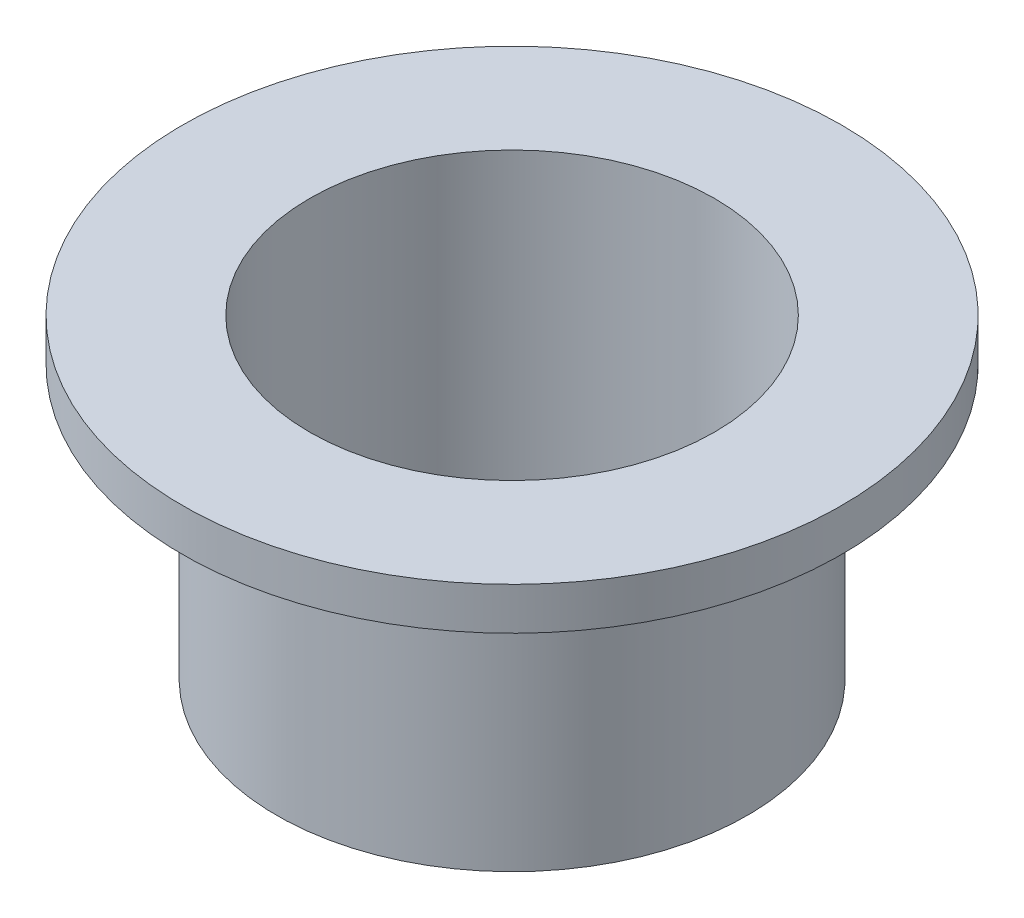
SolidWorks part; units mm, degrees
ref_plane "Front Plane" through (0, 0, 0) normal (1, 0, 0) x (0, 1, 0)
ref_plane "Top Plane" through (0, 0, 0) normal (0, 0, 1) x (0, 1, 0)
ref_plane "Right Plane" through (0, 0, 0) normal (0, 1, 0) x (-1, 0, 0)
sketch "Sketch1" plane through (0, 0, 0) normal (0, 0, 1) x (0, 1, 0)
  line L0 (-147.9957, 0) -> (141.5446, 0) construction
  line L1 (0, 129.9706) -> (0, -121.2427) construction
  line L2 (-58, 50) -> (0, 50)
  line L3 (0, 50) -> (0, 70)
  line L4 (0, 70) -> (9, 70)
  line L5 (9, 70) -> (9, 43)
  line L6 (9, 43) -> (-58, 43)
  line L7 (-58, 43) -> (-58, 50)
  point P7 (4.5, 70)
  dimension "D1" = 67
  dimension "D2" = 9
  dimension "D3" = 100
  dimension "D4" = 140
  dimension "D5" = 43
revolve "Revolve1" add sketch "Sketch1" angle 360 about L0
